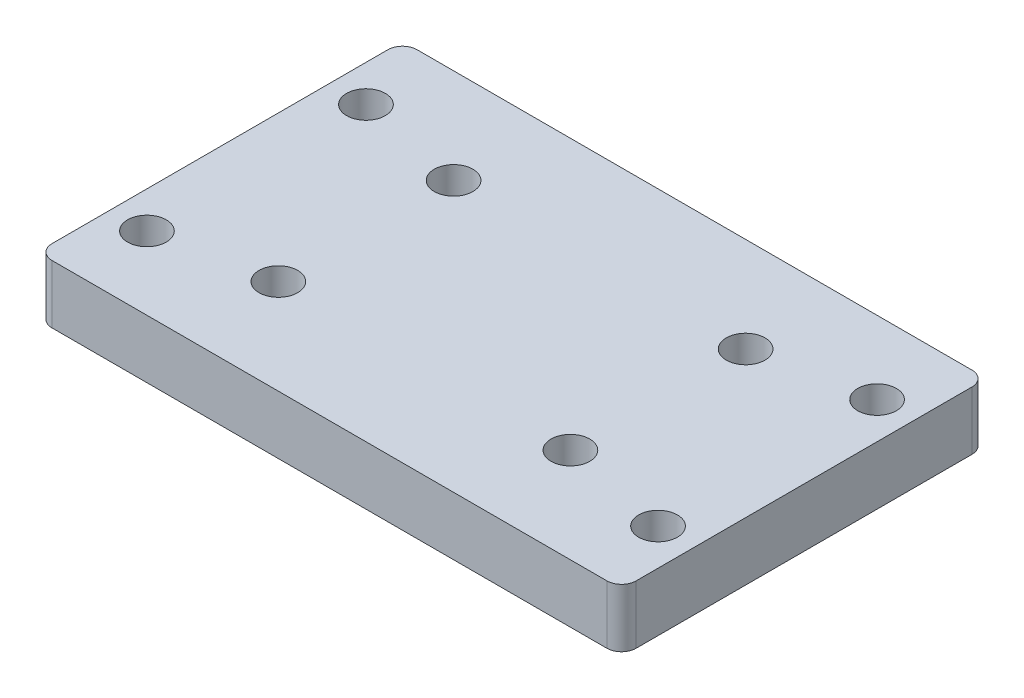
SolidWorks part; units mm, degrees
ref_plane "Front Plane" through (0, 0, 0) normal (0, 0, 1) x (1, 0, 0)
ref_plane "Top Plane" through (0, 0, 0) normal (0, 1, 0) x (1, 0, 0)
ref_plane "Right Plane" through (0, 0, 0) normal (1, 0, 0) x (0, 0, -1)
sketch "Sketch1" plane through (0, 0, 0) normal (0, 1, 0) x (1, 0, 0)
  line L0 (0, -55) -> (0, 55) construction
  line L1 (40, -25) -> (-40, -25)
  line L2 (40, -25) -> (40, 25)
  line L3 (40, 25) -> (-40, 25)
  line L4 (-40, -25) -> (-40, 25)
  line L5 (40, -25) -> (-40, 25) construction
  line L6 (40, 25) -> (-40, -25) construction
  line L7 (-55, 0) -> (55, 0) construction
  dimension "D1" = 40
  dimension "D2" = 25
  dimension "D7" = 80
  dimension "D8" = 50
extrude "Boss-Extrude1" add sketch "Sketch1" along normal blind 8
fillet "Fillet1" radius 2 4 edges at (40, 4, 25) (40, 4, -25) (-40, 4, -25) (-40, 4, 25)
hole_wizard "M5 Clearance Hole1" positions "Sketch3" profile "Sketch2" hole size "M5" standard "ISO"
sketch "Sketch3" plane through (0, 8, 0) normal (0, 1, 0) x (1, 0, 0)
  line L0 (-42.2687, 0) -> (56.8217, 0) construction
  line L1 (-4.4, 0) -> (4.4, 0) construction
  line L3 (0, 18.8846) -> (0, -31.0081) construction
  line L4 (0, -4.4) -> (0, 4.4) construction
  point P0 (-35, 15)
  point P2 (-20, 12)
  point P20 (-20, -12)
  point P21 (-35, -15)
  point P22 (35, -15)
  point P23 (20, -12)
  point P24 (20, 12)
  point P25 (35, 15)
  dimension "D1" = 15
  dimension "D2" = 35
  dimension "D3" = 20
  dimension "D4" = 12
sketch "Sketch2" plane through (-35, 8, -15) normal (1, 0, 0) x (0, 0, 1)
  line L0 (0, 0) -> (0, 9.5923)
  line L1 (0, 9.5923) -> (2.65, 8)
  line L2 (2.65, 8) -> (2.65, 0)
  line L5 (2.65, 0) -> (0, 0)
  line L10 (0, 9.5923) -> (-2.65, 8) construction
  line L11 (0, -6.35) -> (0, 107.95) construction
  dimension "Hole Dia." = 5.3
  dimension "Hole Depth" = 8
  dimension "Drill Angle" = 118
